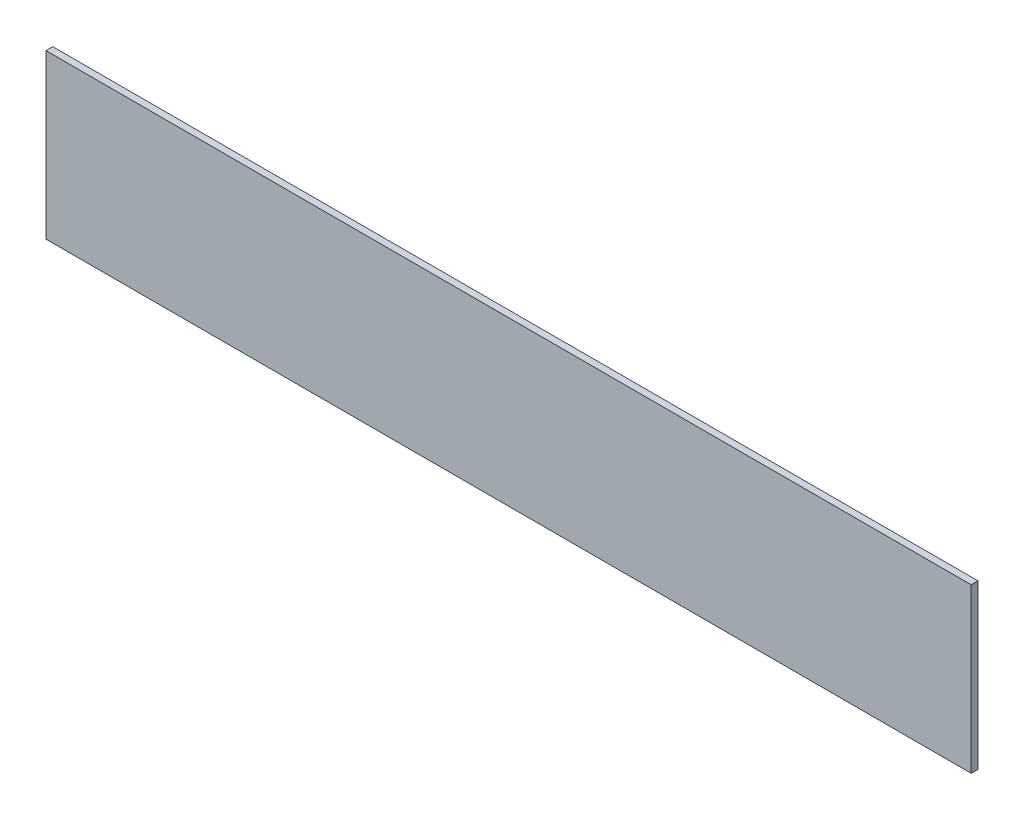
SolidWorks part; units mm, degrees
material "Pine"
ref_plane "Front Plane" through (0, 0, 0) normal (0, 0, 1) x (1, 0, 0)
ref_plane "Top Plane" through (0, 0, 0) normal (0, 1, 0) x (1, 0, 0)
ref_plane "Right Plane" through (0, 0, 0) normal (1, 0, 0) x (0, 0, -1)
sketch "Sketch1" plane through (0, 0, 0) normal (0, 0, 1) x (1, 0, 0)
  line L1 (-863.6, -152.4) -> (863.6, -152.4)
  line L2 (-863.6, -152.4) -> (-863.6, 152.4)
  line L3 (-863.6, 152.4) -> (863.6, 152.4)
  line L4 (863.6, -152.4) -> (863.6, 152.4)
  line L5 (-863.6, -152.4) -> (863.6, 152.4) construction
  line L6 (-863.6, 152.4) -> (863.6, -152.4) construction
  point P0 (0, 0)
  dimension "D1" = 1727.2
  dimension "D2" = 304.8
extrude "Boss-Extrude1" add sketch "Sketch1" along normal mid plane 12.7 contours L3 L4 L1 L2
